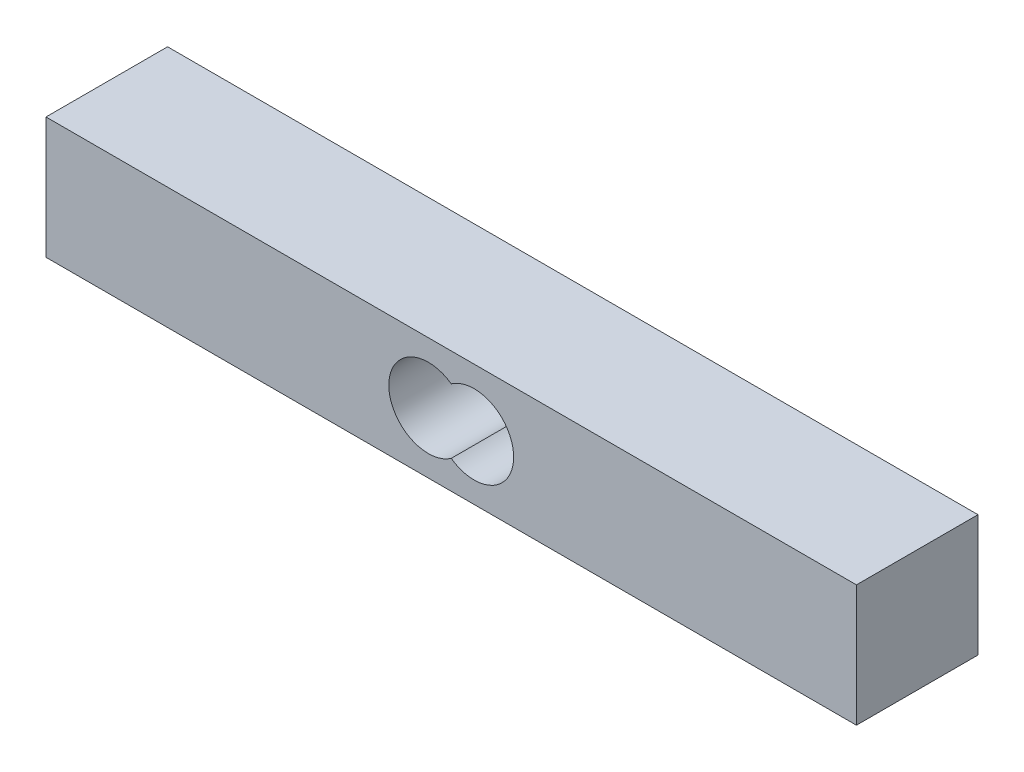
SolidWorks part; units mm, degrees
ref_plane "Front" through (0, 0, 0) normal (0, 0, 1) x (1, 0, 0)
ref_plane "Top" through (0, 0, 0) normal (0, 1, 0) x (1, 0, 0)
ref_plane "Right" through (0, 0, 0) normal (1, 0, 0) x (0, 0, -1)
sketch "Croquis1" plane through (0, 0, 0) normal (0, 1, 0) x (1, 0, 0)
  line L1 (0, 0) -> (80, 0)
  line L2 (0, 0) -> (0, 12)
  line L3 (0, 12) -> (80, 12)
  line L4 (80, 0) -> (80, 12)
  dimension "D1" = 80
  dimension "D2" = 12
extrude "Saliente-Extruir1" add sketch "Croquis1" along normal blind 12
sketch "Croquis2" plane through (0, 0, 0) normal (0, 0, 1) x (1, 0, 0)
  line L0 (40, 12) -> (40, 9.1859) construction
  line L1 (0, 12) -> (80, 12) construction
  line L2 (0, 0) -> (80, 0) construction
  line L3 (0, 6) -> (41.6468, 6) construction
  line L4 (0, 12) -> (0, 0) construction
  line L5 (80, 12) -> (80, 0) construction
  line L6 (40, 2.8141) -> (40, 0) construction
  line L7 (46.1635, 6) -> (80, 6) construction
  arc A0 (40, 2.8141) -> (40, 9.1859) centre (42.2584, 6) ccw
  arc A1 (40, 2.8141) -> (40, 9.1859) centre (37.7416, 6) cw
extrude "Cortar-Extruir1" cut sketch "Croquis2" against normal blind 12
